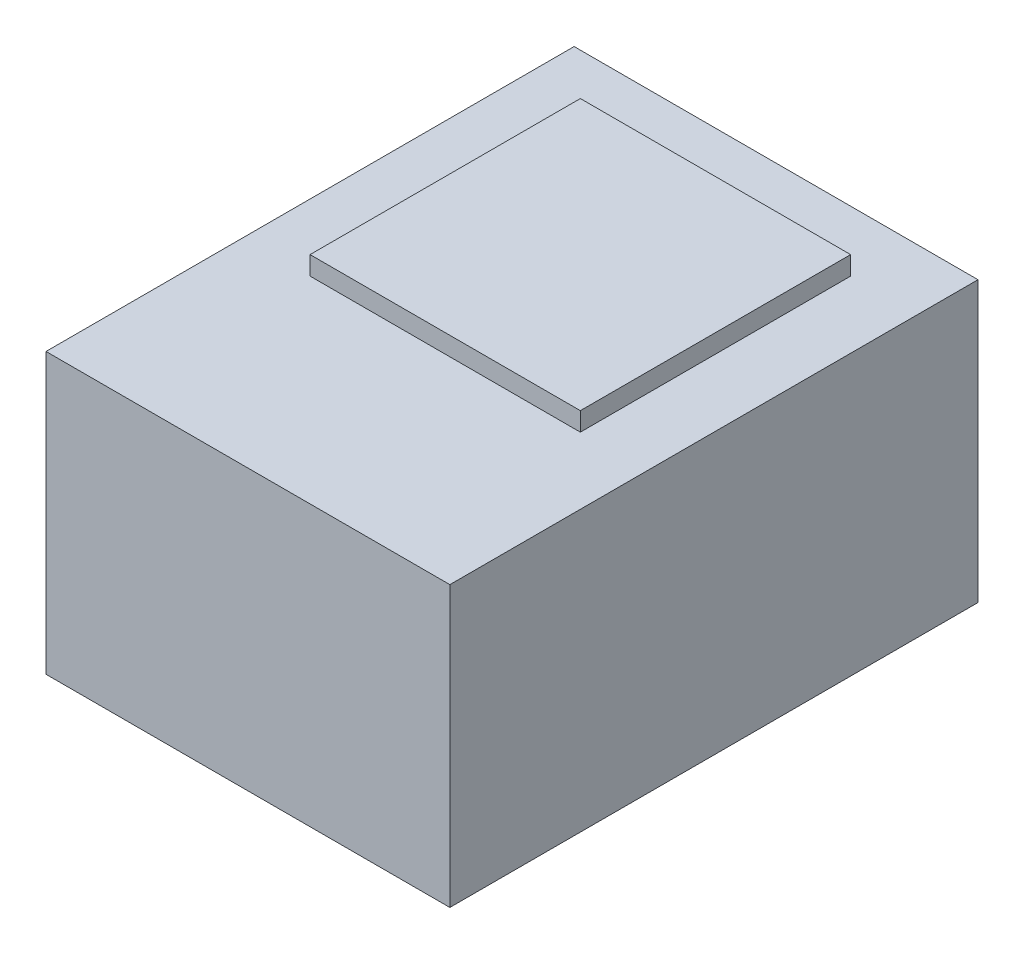
SolidWorks part; units mm, degrees
ref_plane "Front Plane" through (0, 0, 0) normal (0, 0, 1) x (1, 0, 0)
ref_plane "Top Plane" through (0, 0, 0) normal (0, 1, 0) x (1, 0, 0)
ref_plane "Right Plane" through (0, 0, 0) normal (1, 0, 0) x (0, 0, -1)
sketch "Sketch1" plane through (0, 0, 0) normal (0, 1, 0) x (1, 0, 0)
  line L1 (-0.65, 0.85) -> (0.65, 0.85)
  line L2 (-0.65, 0.85) -> (-0.65, -0.85)
  line L3 (-0.65, -0.85) -> (0.65, -0.85)
  line L4 (0.65, 0.85) -> (0.65, -0.85)
  line L5 (-0.65, 0.85) -> (0.65, -0.85) construction
  line L6 (-0.65, -0.85) -> (0.65, 0.85) construction
  point P0 (0, 0)
  dimension "D1" = 1.7
  dimension "D2" = 1.3
extrude "Boss-Extrude1" add sketch "Sketch1" along normal blind 0.9
sketch "Sketch2" plane through (0, 0, 0) normal (0, -1, 0) x (1, 0, 0)
  line L0 (0, 0.85) -> (0, -0.85) construction
  line L1 (-0.525, 0.7864) -> (-0.125, 0.7864)
  line L2 (-0.525, 0.7864) -> (-0.525, -0.7136)
  line L3 (-0.525, -0.7136) -> (-0.125, -0.7136)
  line L4 (-0.125, 0.7864) -> (-0.125, -0.7136)
  line L5 (-0.525, 0.7864) -> (-0.125, -0.7136) construction
  line L6 (-0.525, -0.7136) -> (-0.125, 0.7864) construction
  line L7 (-0.65, 0.85) -> (0.65, 0.85) construction
  line L8 (0.65, -0.85) -> (-0.65, -0.85) construction
  line L9 (0.125, 0.7864) -> (0.525, 0.7864)
  line L10 (0.125, 0.7864) -> (0.125, -0.7136)
  line L11 (0.125, -0.7136) -> (0.525, -0.7136)
  line L12 (0.525, 0.7864) -> (0.525, -0.7136)
  line L13 (0.125, 0.7864) -> (0.525, -0.7136) construction
  line L14 (0.125, -0.7136) -> (0.525, 0.7864) construction
  line L15 (-0.125, -0.7136) -> (0, -0.7136) construction
  line L16 (0, -0.7136) -> (0.125, -0.7136) construction
  point P0 (-0.325, 0.0364)
  point P11 (0.325, 0.0364)
  dimension "D1" = 1.5
  dimension "D2" = 0.4
  dimension "D3" = 0.4
  dimension "D4" = 0.25
extrude "Boss-Extrude2" add sketch "Sketch2" along normal blind 0.06
sketch "Sketch3" plane through (0, 0.9, 0) normal (0, 1, 0) x (1, 0, 0)
  line L0 (-0.65, 0.85) -> (-0.65, -0.85) construction
  line L1 (-0.435, 0.655) -> (0.435, 0.655)
  line L2 (-0.435, 0.655) -> (-0.435, -0.215)
  line L3 (-0.435, -0.215) -> (0.435, -0.215)
  line L4 (0.435, 0.655) -> (0.435, -0.215)
  line L5 (-0.435, 0.655) -> (0.435, -0.215) construction
  line L6 (-0.435, -0.215) -> (0.435, 0.655) construction
  line L8 (0.65, 0.85) -> (-0.65, 0.85) construction
  point P0 (0, 0.22)
  dimension "D1" = 0.65
  dimension "D2" = 0.63
  dimension "D3" = 0.87
  dimension "D4" = 0.87
extrude "Boss-Extrude3" add sketch "Sketch3" along normal blind 0.06 contours L2 L3 L4 L1
sketch "Optical Center" plane through (0, 0.9, 0) normal (0, 1, 0) x (1, 0, 0)
  point P0 (0, 0.22)
